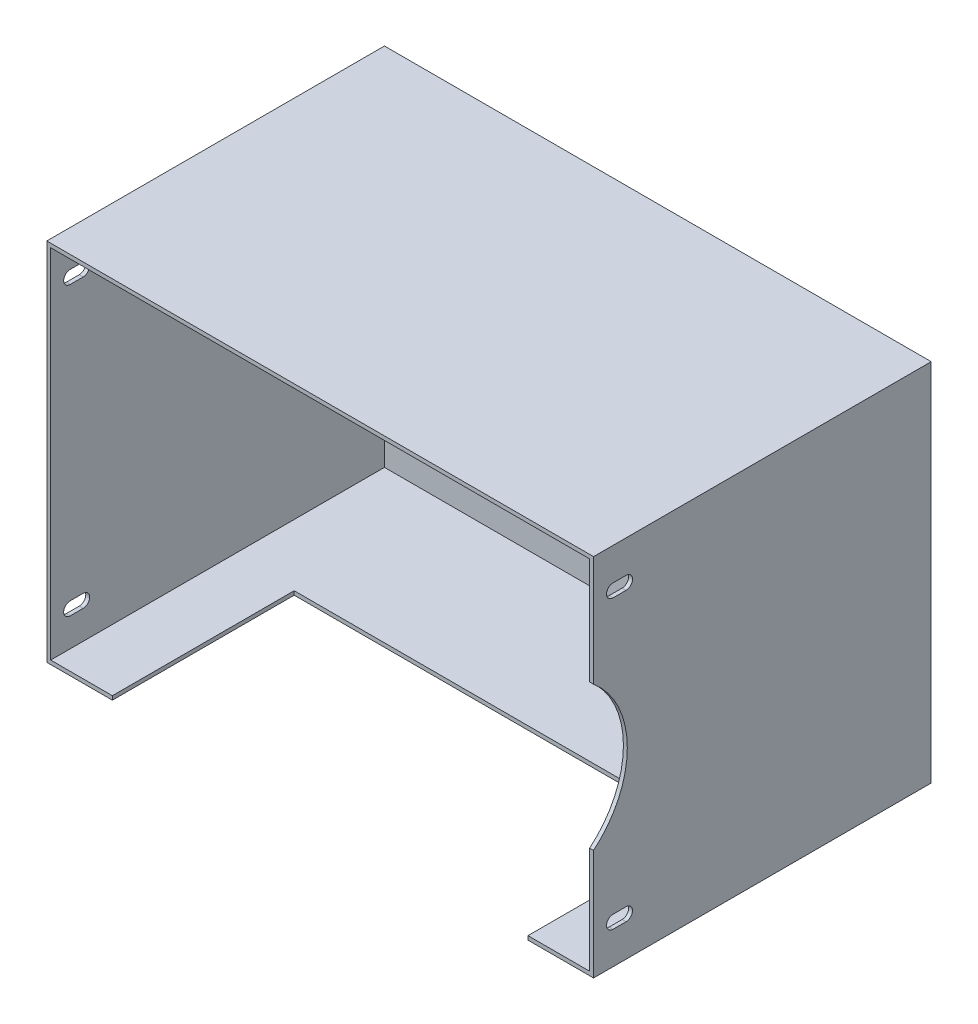
SolidWorks part; units mm, degrees
ref_plane "前视基准面" through (0, 0, 0) normal (0, 0, 1) x (1, 0, 0)
ref_plane "上视基准面" through (0, 0, 0) normal (0, 1, 0) x (1, 0, 0)
ref_plane "右视基准面" through (0, 0, 0) normal (1, 0, 0) x (0, 0, -1)
sketch "草图1" plane through (0, 0, 0) normal (0, 0, 1) x (1, 0, 0)
  line L1 (-105.25, 70.25) -> (105.25, 70.25)
  line L2 (-105.25, 70.25) -> (-105.25, -70.25)
  line L3 (-105.25, -70.25) -> (105.25, -70.25)
  line L4 (105.25, 70.25) -> (105.25, -70.25)
  line L5 (-105.25, 70.25) -> (105.25, -70.25) construction
  line L6 (-105.25, -70.25) -> (105.25, 70.25) construction
  point P0 (0, 0)
  dimension "D1" = 210.5
  dimension "D2" = 140.5
extrude "凸台-拉伸1" add sketch "草图1" along normal blind 130
shell "抽壳1" thickness 1.5
sketch "草图2" plane through (105.25, 0, 0) normal (1, 0, 0) x (0, 0, -1)
  line L0 (-130, 0) -> (-117, 0) construction
  line L1 (-130, -70.25) -> (-130, 70.25) construction
  line L2 (-130, 27.6948) -> (-130, 0) construction
  line L3 (-130, 0) -> (-130, -27.6948) construction
  line L4 (-130, 27.6948) -> (-130, -27.6948)
  arc A0 (-130, 27.6948) -> (-130, -27.6948) centre (-153, 0) cw
  dimension "D3" = 36
  dimension "D1" = 13
extrude "切除-拉伸2" cut sketch "草图2" against normal up to next
sketch "草图3" plane through (0, -70.25, 0) normal (0, -1, 0) x (1, 0, 0)
  line L0 (-105.25, 130) -> (105.25, 130) construction
  line L1 (80, 130) -> (-80, 130)
  line L2 (80, 130) -> (80, 60)
  line L3 (80, 60) -> (-80, 60)
  line L4 (-80, 130) -> (-80, 60)
  line L5 (-105.25, 130) -> (-105.25, 0) construction
  line L6 (105.25, 130) -> (105.25, 0) construction
  dimension "D1" = 160
  dimension "D2" = 70
  dimension "D3" = 25.25
  dimension "D4" = 25.25
extrude "切除-拉伸3" cut sketch "草图3" against normal up to next
sketch "草图4" plane through (105.25, 0, 0) normal (1, 0, 0) x (0, 0, -1)
  line L0 (-122.5, 55.25) -> (-117.5, 55.25) construction
  line L1 (-122.5, 57.75) -> (-117.5, 57.75)
  line L2 (-122.5, 52.75) -> (-117.5, 52.75)
  line L3 (0, 0) -> (-156.4305, 0) construction
  line L4 (-130, 27.6948) -> (-130, 70.25) construction
  line L5 (-122.5, -55.25) -> (-117.5, -55.25) construction
  line L6 (-122.5, -57.75) -> (-117.5, -57.75)
  line L7 (-122.5, -52.75) -> (-117.5, -52.75)
  line L8 (-130, 70.25) -> (0, 70.25) construction
  arc A0 (-122.5, 57.75) -> (-122.5, 52.75) centre (-122.5, 55.25) ccw
  arc A1 (-117.5, 52.75) -> (-117.5, 57.75) centre (-117.5, 55.25) ccw
  arc A2 (-122.5, -57.75) -> (-122.5, -52.75) centre (-122.5, -55.25) cw
  arc A3 (-117.5, -52.75) -> (-117.5, -57.75) centre (-117.5, -55.25) cw
  point P2 (-120, 55.25)
  point P14 (-120, -55.25)
  dimension "D1" = 2.5
  dimension "D2" = 10
  dimension "D3" = 2.5
  dimension "D4" = 15
extrude "切除-拉伸4" cut sketch "草图4" against normal through all both and the other way through all
